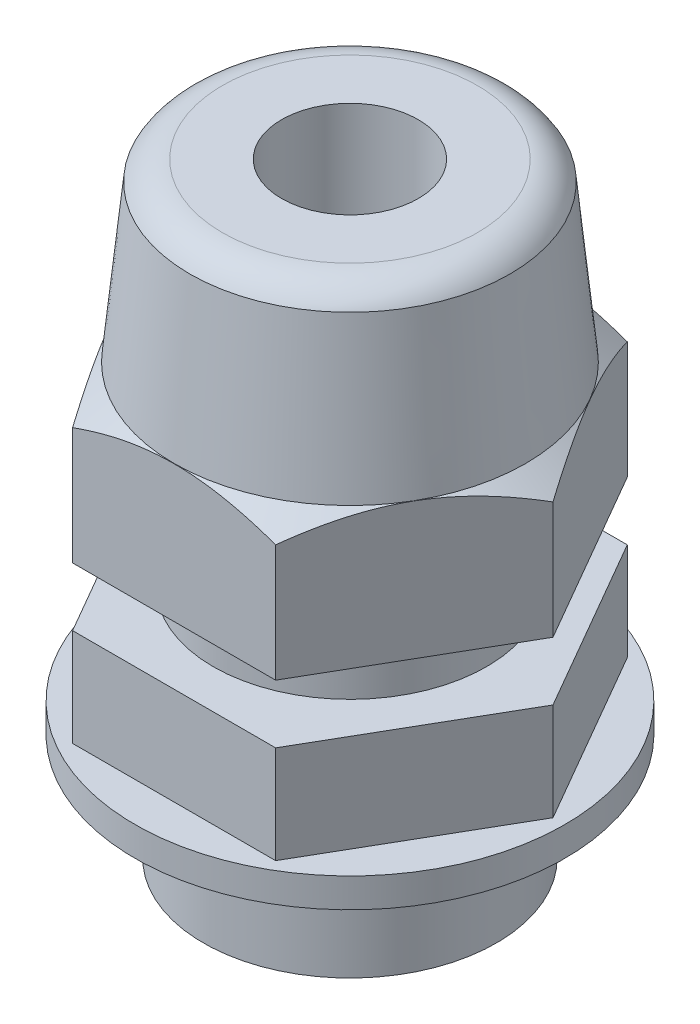
SolidWorks part; units mm, degrees
ref_plane "Спереди" through (0, 0, 0) normal (0, 0, 1) x (1, 0, 0)
ref_plane "Сверху" through (0, 0, 0) normal (0, 1, 0) x (1, 0, 0)
ref_plane "Справа" through (0, 0, 0) normal (1, 0, 0) x (0, 0, -1)
sketch "Эскиз1" plane through (0, 0, 0) normal (0, 1, 0) x (1, 0, 0)
  line L0 (-5.1962, 9) -> (5.1962, 9)
  line L1 (5.1962, 9) -> (10.3923, 0)
  line L2 (10.3923, 0) -> (5.1962, -9)
  line L3 (5.1962, -9) -> (-5.1962, -9)
  line L4 (-5.1962, -9) -> (-10.3923, 0)
  line L5 (-10.3923, 0) -> (-5.1962, 9)
  dimension "D1" = 9
  dimension "D2" = 120
  dimension "D3" = 120
  dimension "D4" = 120
  dimension "D5" = 120
  dimension "D6" = 9
  dimension "D7" = 9
  dimension "D8" = 9
  dimension "D9" = 9
  dimension "D10" = 9
extrude "Вытянуть1" add sketch "Эскиз1" against normal blind 24
ref_axis "Ось1" through (0, 9.9808, 0) along (0, -1, 0)
sketch "Эскиз2" plane through (0, 0, 0) normal (0, 0, 1) x (1, 0, 0)
  line L0 (8.9923, -9) -> (10.3923, -10)
  line L1 (10.3923, -24) -> (10.3923, 0) construction
  line L2 (10.3923, -10) -> (11.8814, -10)
  line L3 (11.8814, -10) -> (11.8814, 2.2315)
  line L4 (8.9923, -9) -> (8.1923, -1)
  line L5 (5.1962, 0) -> (10.3923, 0) construction
  line L6 (6.3923, 0) -> (6.3923, 2.2315)
  line L7 (6.3923, 2.2315) -> (11.8814, 2.2315)
  arc A0 (8.1923, -1) -> (6.3923, 0) centre (6.4596, -1.9989) ccw
  dimension "D7" = 2
  dimension "D1" = 1.4
  dimension "D2" = 9
  dimension "D3" = 10
  dimension "D4" = 4
  dimension "D5" = 2.2
  dimension "D6" = 1
revolve "Вырез-Повернуть1" cut sketch "Эскиз2" angle 360 about axis through (0, 9.9808, 0) along (0, -1, 0)
sketch "Эскиз3" plane through (0, 0, 0) normal (0, 0, 1) x (1, 0, 0)
  line L0 (10.3923, -24) -> (10.3923, -10) construction
  line L1 (10.3923, -19) -> (7, -19)
  line L2 (10.3923, -19) -> (10.3923, -16)
  line L3 (10.3923, -16) -> (7, -16)
  line L4 (7, -19) -> (7, -16)
  line L5 (5.1962, -24) -> (10.3923, -24) construction
  line L6 (-5.1962, -24) -> (5.1962, -24) construction
  point P8 (0, -24)
  dimension "D1" = 5
  dimension "D2" = 3
  dimension "D3" = 7
revolve "Вырез-Повернуть2" cut sketch "Эскиз3" angle 360 about axis through (0, 9.9808, 0) along (0, -1, 0)
sketch "Эскиз4" plane through (0, -24, 0) normal (0, -1, 0) x (1, 0, 0)
  circle A0 centre (0, 0) radius 7.5
  dimension "D1" = 15
extrude "Вытянуть2" add sketch "Эскиз4" along normal blind 7
sketch "Эскиз5" plane through (0, -31, 0) normal (0, -1, 0) x (1, 0, 0)
  circle A0 centre (0, 0) radius 5
  dimension "D1" = 10
extrude "Вырез-Вытянуть1" cut sketch "Эскиз5" against normal through all
sketch "Эскиз6" plane through (0, 0, 0) normal (0, 1, 0) x (-1, 0, 0)
  circle A0 centre (0, 0) radius 5
  circle A1 centre (0, 0) radius 3.5
  circle A2 centre (0, 0) radius 5 construction
  dimension "D1" = 7
extrude "Вытянуть3" add sketch "Эскиз6" against normal blind 12
chamfer "Фаска1" distance 5.5 angle 15 1 edges at (0, -12, 5)
sketch "Эскиз7" plane through (0, -24, 0) normal (0, -1, 0) x (1, 0, 0)
  circle A0 centre (0, 0) radius 11
  dimension "D1" = 22
extrude "Вытянуть4" add sketch "Эскиз7" along normal blind 1.5
